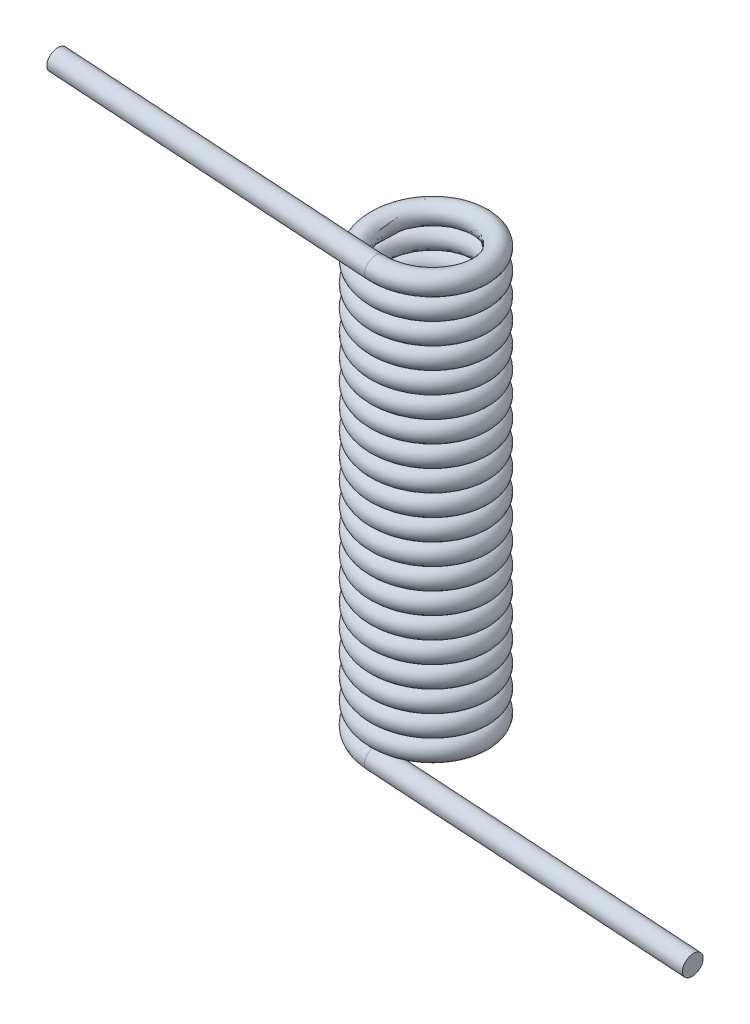
SolidWorks part; units mm, degrees
ref_plane "Front Plane" through (0, 0, 0) normal (0, 0, 1) x (1, 0, 0)
ref_plane "Top Plane" through (0, 0, 0) normal (0, 1, 0) x (1, 0, 0)
ref_plane "Right Plane" through (0, 0, 0) normal (1, 0, 0) x (0, 0, -1)
sketch "Sketch1" plane through (0, 0, 0) normal (0, 0, 1) x (1, 0, 0)
  line L0 (0, -13.97) -> (0, 13.97) construction
  dimension "D1" = 27.94
sketch "Sketch2" plane through (0, 0, 0) normal (0, 0, 1) x (1, 0, 0)
  line L0 (0, -13.97) -> (-3.683, -13.97) construction
  line L1 (-3.683, -13.97) -> (-3.683, -13.335) construction
  line L2 (0, -13.97) -> (0, 13.97) construction
  circle A0 centre (-3.048, -13.335) radius 0.635
  point P5 (0, 0)
  dimension "D1" = 1.27
  dimension "D2" = 3.683
sketch "Sketch3" plane through (0, 0, 0) normal (0, 0, 1) x (1, 0, 0)
  circle A0 centre (-3.048, -13.335) radius 0.635
  circle A1 centre (-3.048, -13.335) radius 0.635 construction
ref_plane "Plane2" through (0, -13.97, 0) normal (0, 1, 0) x (1, 0, 0)
sketch "Sketch4" plane through (0, -13.97, 0) normal (0, 1, 0) x (1, 0, 0)
  circle A0 centre (0, 0) radius 3.048
  point P3 (-3.048, 0)
  point P5 (-3.048, 0)
curve "Helix/Spiral3" pitch 1.27 height 25.4 turns 20
ref_plane "Plane3" through (0, -13.97, 3.048) normal (-0.9978, 0.0662, 0) x (0, 0, 1)
sweep "Sweep3" add path "Helix/Spiral3" circular profile diameter 1.2446 parameters "D3"=1.2446
sketch "Sketch35" plane through (-0.7547, 0.05, 0) normal (-0.9978, 0.0662, 0) x (0, 0, 1)
  circle A1 centre (3.048, 11.405) radius 0.6223
  circle A2 centre (3.048, 11.405) radius 0.6223
  dimension "D1" = 0
extrude "Boss-Extrude1" add sketch "Sketch35" along normal blind 19.05
sketch "Sketch36" plane through (0.9224, -0.0612, 0) normal (0.9978, -0.0662, 0) x (0, 0, -1)
  circle A1 centre (-3.048, -13.9394) radius 0.6223
  circle A2 centre (-3.048, -13.9394) radius 0.6223
  dimension "D1" = 0
extrude "Boss-Extrude2" add sketch "Sketch36" along normal blind 19.05
equation "\"WireDiameter\"= .049in"
equation "\"D3@Sweep3\"=\"WireDiameter\""
